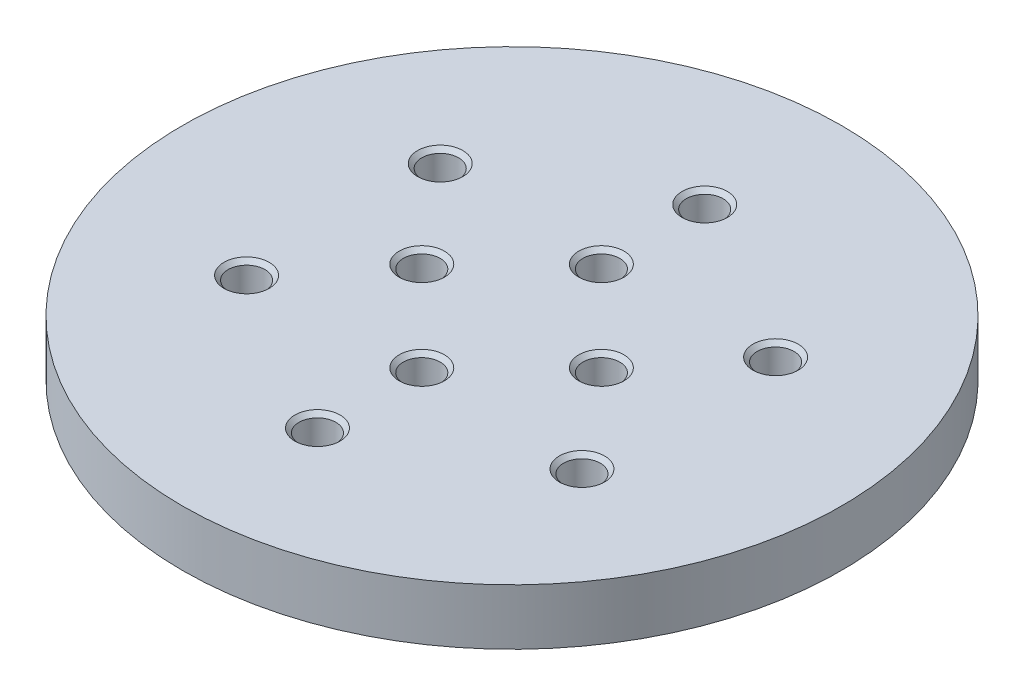
SolidWorks part; units mm, degrees
ref_plane "前视基准面" through (0, 0, 0) normal (0, 0, 1) x (1, 0, 0)
ref_plane "上视基准面" through (0, 0, 0) normal (0, 1, 0) x (1, 0, 0)
ref_plane "右视基准面" through (0, 0, 0) normal (1, 0, 0) x (0, 0, -1)
sketch "草图1" plane through (0, 0, 0) normal (0, 1, 0) x (1, 0, 0)
  circle A0 centre (0, 0) radius 29.5
  dimension "D1" = 59
extrude "凸台-拉伸1" add sketch "草图1" along normal blind 5
sketch "草图2" plane through (0, 5, 0) normal (0, 1, 0) x (1, 0, 0)
  point P0 (0, 8)
  dimension "D1" = 8
hole_wizard "M4 螺纹孔1" positions "草图2" profile "草图3" tap size "M4" standard "DIN"
sketch "草图3" plane through (0, 5, -8) normal (1, 0, 0) x (0, 0, 1)
  line L0 (0, 0) -> (0, 11.0914)
  line L1 (0, 11.0914) -> (1.65, 10.1)
  line L2 (1.65, 10.1) -> (1.65, 0.375)
  line L3 (1.65, 0.375) -> (2.025, 0)
  line L5 (2.025, 0) -> (0, 0)
  line L6 (-1.65, 0.375) -> (-2.025, 0) construction
  line L10 (0, 11.0914) -> (-1.65, 10.1) construction
  line L11 (0, -6.35) -> (0, 107.95) construction
  dimension "螺纹孔钻头直径" = 3.3
  dimension "螺纹孔钻头深度" = 10.1
  dimension "近端锥形沉头孔直径" = 4.05
  dimension "近端锥形沉头孔角度" = 90
  dimension "导头角度" = 118
cosmetic thread "孔螺纹线1" parameters "D1"=8, "D2"=4
pattern_circular "阵列(圆周)1" count 4 over 360 about axis through (0, 0, 0.0379) along (0, 1, 0) of "M4 螺纹孔1"
sketch "草图4" plane through (0, 5, 0) normal (0, 1, 0) x (1, 0, 0)
  point P0 (0, 17.25)
  dimension "D1" = 17.25
hole_wizard "M4 螺纹孔2" positions "草图4" profile "草图5" tap size "M4" standard "DIN"
sketch "草图5" plane through (0, 5, -17.25) normal (1, 0, 0) x (0, 0, 1)
  line L0 (0, 0) -> (0, 11.0914)
  line L1 (0, 11.0914) -> (1.65, 10.1)
  line L2 (1.65, 10.1) -> (1.65, 0.375)
  line L3 (1.65, 0.375) -> (2.025, 0)
  line L5 (2.025, 0) -> (0, 0)
  line L6 (-1.65, 0.375) -> (-2.025, 0) construction
  line L10 (0, 11.0914) -> (-1.65, 10.1) construction
  line L11 (0, -6.35) -> (0, 107.95) construction
  dimension "螺纹孔钻头直径" = 3.3
  dimension "螺纹孔钻头深度" = 10.1
  dimension "近端锥形沉头孔直径" = 4.05
  dimension "近端锥形沉头孔角度" = 90
  dimension "导头角度" = 118
cosmetic thread "孔螺纹线2" parameters "D1"=8, "D2"=4
pattern_circular "阵列(圆周)2" count 6 over 360 about axis through (0, 0, 0.0825) along (0, 1, 0) of "M4 螺纹孔2"
